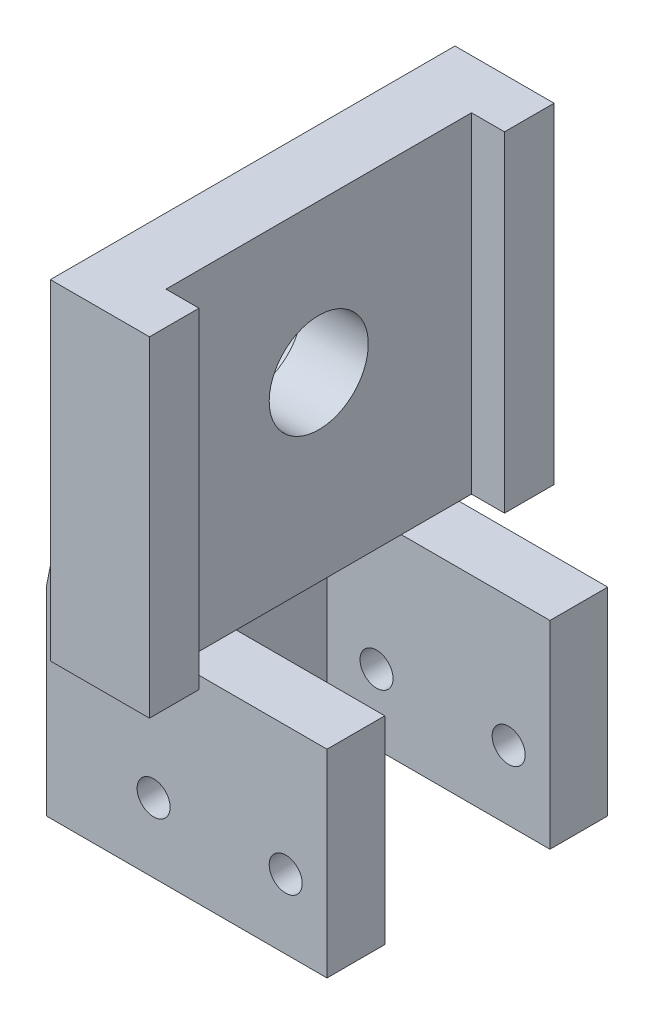
SolidWorks part; units mm, degrees
ref_plane "Front Plane" through (0, 0, 0) normal (0, 0, 1) x (1, 0, 0)
ref_plane "Top Plane" through (0, 0, 0) normal (0, 1, 0) x (1, 0, 0)
ref_plane "Right Plane" through (0, 0, 0) normal (1, 0, 0) x (0, 0, -1)
sketch "Sketch2" plane through (0, 0, 0) normal (0, 1, 0) x (1, 0, 0)
  line L0 (-29.5197, 7.1601) -> (-29.5197, -17.3399)
  line L1 (-29.5197, -17.3399) -> (-23.5197, -17.3399)
  line L2 (-23.5197, -17.3399) -> (-23.5197, -14.3399)
  line L3 (-23.5197, -14.3399) -> (-25.5197, -14.3399)
  line L4 (-25.5197, -14.3399) -> (-25.5197, 4.1601)
  line L5 (-25.5197, 4.1601) -> (-23.5197, 4.1601)
  line L6 (-23.5197, 4.1601) -> (-23.5197, 7.1601)
  line L7 (-23.5197, 7.1601) -> (-29.5197, 7.1601)
  dimension "D1" = 18.5
  dimension "D2" = 2
  dimension "D3" = 4
  dimension "D4" = 3
extrude "Boss-Extrude1" add sketch "Sketch2" along normal blind 20
sketch "Sketch3" plane through (-29.5197, 0, 0) normal (-1, 0, 0) x (0, 0, 1)
  line L0 (-7.1601, 20) -> (17.3399, 20) construction
  line L1 (17.3399, 20) -> (17.3399, 0) construction
  circle A0 centre (5.0899, 11) radius 3
  dimension "D2" = 6
  dimension "D3" = 12.25
  dimension "D1" = 9
extrude "Cut-Extrude1" cut sketch "Sketch3" against normal blind 4
sketch "Sketch4" plane through (0, 0, 0) normal (0, -1, 0) x (1, 0, 0)
  line L0 (-29.5197, -7.1601) -> (-29.5197, 17.3399) construction
  line L1 (-16.5197, -3.4101) -> (-33.5197, -3.4101)
  line L2 (-16.5197, -3.4101) -> (-16.5197, 0.0899)
  line L3 (-16.5197, 13.5899) -> (-33.5197, 13.5899)
  line L4 (-33.5197, -3.4101) -> (-33.5197, 13.5899)
  line L5 (-23.5197, -7.1601) -> (-29.5197, -7.1601) construction
  line L6 (-16.5197, 0.0899) -> (-30.0197, 0.0899)
  line L7 (-30.0197, 0.0899) -> (-30.0197, 10.0899)
  line L8 (-30.0197, 10.0899) -> (-16.5197, 10.0899)
  line L9 (-16.5197, 10.0899) -> (-16.5197, 13.5899)
  dimension "D1" = 13
  dimension "D2" = 17
  dimension "D3" = 17
  dimension "D4" = 3.75
  dimension "D5" = 3.5
  dimension "D6" = 3.5
  dimension "D7" = 3.5
extrude "Boss-Extrude2" add sketch "Sketch4" along normal blind 12
sketch "Sketch5" plane through (0, 0, -3.4101) normal (0, 0, -1) x (-1, 0, 0)
  line L0 (16.5197, -12) -> (16.5197, 0) construction
  line L1 (33.5197, -12) -> (16.5197, -12) construction
  circle A0 centre (19.0197, -7.8) radius 1
  circle A1 centre (27.0197, -7.8) radius 1
  dimension "D1" = 2
  dimension "D4" = 8
  dimension "D2" = 2.5
  dimension "D3" = 4.2
extrude "Cut-Extrude2" cut sketch "Sketch5" against normal blind 17
sketch "Sketch6" plane through (0, 0, -3.4101) normal (0, 0, -1) x (-1, 0, 0)
  line L0 (33.5197, 0) -> (29.5197, 19.9572)
  line L1 (29.5197, 19.9572) -> (29.5197, 0)
  line L2 (33.5197, 0) -> (29.5197, 0) construction
  line L3 (29.5197, 0) -> (33.5197, 0)
  line L4 (29.5197, 20) -> (29.5197, 0) construction
  point P3 (29.8419, 19.2195)
  point P7 (29.7563, 19.8867)
  point P8 (0, 0)
  point P9 (29.7296, 20.0147)
  point P10 (0, 0)
  point P13 (30.0012, 19.7476)
  point P14 (29.5197, 0)
  point P16 (29.5197, 19.985)
  point P17 (29.5197, 19.9963)
  point P20 (0, 0)
  point P21 (29.5197, 19.9572)
sketch "Sketch10" plane through (-29.5197, 0, 0) normal (-1, 0, 0) x (0, 0, 1)
  circle A0 centre (5.0899, 11) radius 6.25
  circle A1 centre (5.0899, 11) radius 3 construction
  dimension "D1" = 12.5
extrude "Boss-Extrude3" add sketch "Sketch6" against normal blind 17
extrude "Cut-Extrude3" cut sketch "Sketch10" along normal blind 4
sketch "Sketch11" plane through (0, 0, 10.0899) normal (0, 0, -1) x (-1, 0, 0)
  line L0 (25.5197, 0) -> (30.0197, -3.6474)
  line L1 (30.0197, -12) -> (30.0197, 0) construction
  line L2 (30.0197, -3.6474) -> (30.0197, 0)
  line L3 (30.0197, 0) -> (25.5197, 0)
  point P5 (25.5197, 0.009)
  point P7 (30.0197, -3.6474)
extrude "Boss-Extrude4" add sketch "Sketch11" along normal blind 10
